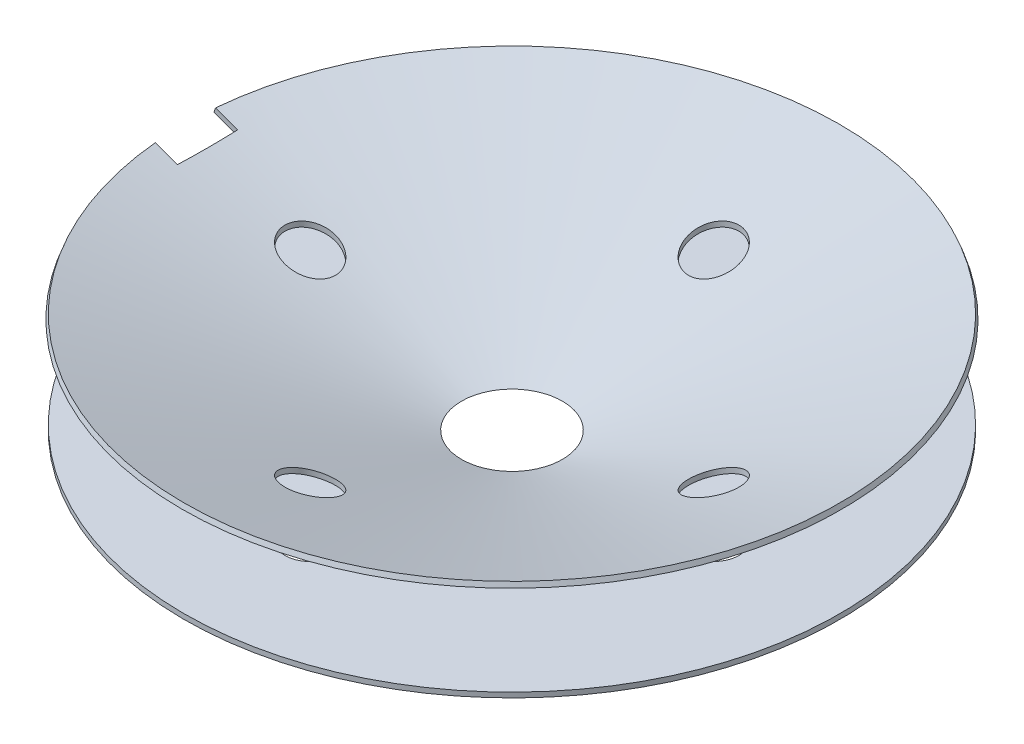
SolidWorks part; units mm, degrees
ref_plane "Front Plane" through (0, 0, 0) normal (0, 0, 1) x (1, 0, 0)
ref_plane "Top Plane" through (0, 0, 0) normal (0, 1, 0) x (1, 0, 0)
ref_plane "Right Plane" through (0, 0, 0) normal (1, 0, 0) x (0, 0, -1)
sketch "Sketch1" plane through (0, 0, 0) normal (0, 0, 1) x (1, 0, 0)
  line L0 (-65, 0) -> (65, 0) construction
  line L1 (-65, 0) -> (-10, -20.0184)
  line L2 (0, 0) -> (0, -100) construction
  line L3 (-10, -20.0184) -> (-65, -20.0184)
  dimension "D1" = 130
  dimension "D2" = 65
  dimension "D3" = 20
  dimension "D4" = 10
  dimension "D5" = 100
revolve "Revolve-Thin1" add sketch "Sketch1" angle 360 about L2
sketch "Sketch2" plane through (0, 0, 0) normal (0, 1, 0) x (1, 0, 0)
  line L1 (-70.342, 5.9683) -> (-60.342, 5.9683)
  line L2 (-70.342, 5.9683) -> (-70.342, -5.9683)
  line L3 (-70.342, -5.9683) -> (-60.342, -5.9683)
  line L4 (-60.342, 5.9683) -> (-60.342, -5.9683)
  line L5 (-70.342, 5.9683) -> (-60.342, -5.9683) construction
  line L6 (-70.342, -5.9683) -> (-60.342, 5.9683) construction
  circle A0 centre (-40, 0) radius 5
  circle A1 centre (0, 40) radius 5
  circle A2 centre (40, 0) radius 5
  circle A3 centre (0, -40) radius 5
  circle A4 centre (0, 0) radius 65.342 construction
  point P9 (-65.342, 0)
  dimension "D1" = 10
  dimension "D4" = 10
  dimension "D5" = 10
  dimension "D6" = 10
  dimension "D2" = 40
  dimension "D3" = 40
  dimension "D7" = 40
  dimension "D8" = 40
  dimension "D9" = 10
extrude "Cut-Extrude1" cut sketch "Sketch2" against normal through all
